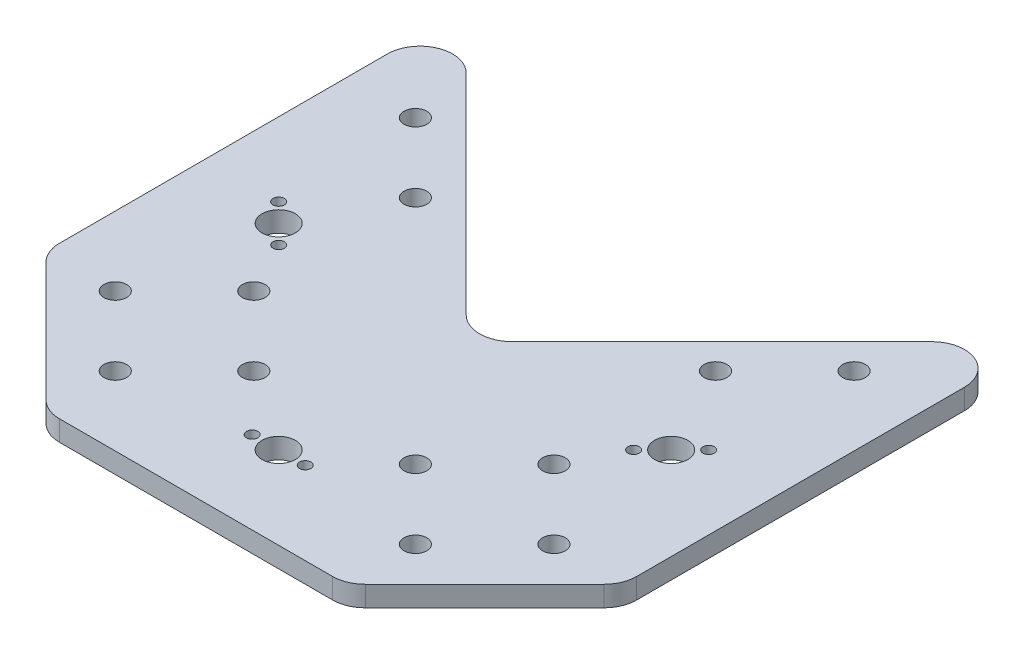
SolidWorks part; units mm, degrees
material "Acrylic (Medium-high impact)"
ref_plane "Front Plane" through (0, 0, 0) normal (0, 0, 1) x (1, 0, 0)
ref_plane "Top Plane" through (0, 0, 0) normal (0, 1, 0) x (1, 0, 0)
ref_plane "Right Plane" through (0, 0, 0) normal (1, 0, 0) x (0, 0, -1)
sketch "Sketch1" plane through (0, 0, 0) normal (0, 1, 0) x (1, 0, 0)
  line L0 (-112.2532, -112.2532) -> (-58.3717, -166.1347)
  line L1 (-112.2532, -112.2532) -> (-26.9408, -26.9408)
  line L2 (58.3717, -166.1347) -> (112.2532, -112.2532)
  line L3 (26.9408, -26.9408) -> (112.2532, -112.2532)
  line L4 (-112.2532, -112.2532) -> (-112.2532, 58.3717)
  line L5 (-112.2532, 58.3717) -> (0, -53.8815)
  line L6 (112.2532, -112.2532) -> (112.2532, 58.3717)
  line L7 (0, -53.8815) -> (112.2532, 58.3717)
  line L8 (-58.3717, -166.1347) -> (58.3717, -166.1347)
  line L9 (0, 0) -> (-53.8815, -53.8815) construction
  line L10 (0, 0) -> (53.8815, -53.8815) construction
  line L11 (-53.8815, -53.8815) -> (0, -107.7631) construction
  line L12 (53.8815, -53.8815) -> (0, -107.7631) construction
  line L13 (-58.3717, -139.194) -> (-85.3124, -112.2532) construction
  line L14 (-58.3717, -139.194) -> (-31.4309, -112.2532) construction
  line L15 (-85.3124, -112.2532) -> (-58.3717, -85.3124) construction
  line L16 (-31.4309, -112.2532) -> (-58.3717, -85.3124) construction
  line L17 (58.3717, -85.3124) -> (85.3124, -112.2532) construction
  line L18 (58.3717, -85.3124) -> (31.4309, -112.2532) construction
  line L19 (85.3124, -112.2532) -> (58.3717, -139.194) construction
  line L20 (31.4309, -112.2532) -> (58.3717, -139.194) construction
  line L21 (0, -53.8815) -> (0, 0) construction
  line L22 (-58.3717, -22.4506) -> (-85.3124, 4.4901) construction
  line L23 (58.3717, -22.4506) -> (85.3124, 4.4901) construction
  circle A0 centre (-85.3124, -112.2532) radius 4.4196
  circle A1 centre (-58.3717, -85.3124) radius 4.4196
  circle A2 centre (-31.4309, -112.2532) radius 4.4196
  circle A3 centre (-58.3717, -139.194) radius 4.4196
  circle A4 centre (31.4309, -112.2532) radius 4.4196
  circle A5 centre (58.3717, -85.3124) radius 4.4196
  circle A6 centre (85.3124, -112.2532) radius 4.4196
  circle A7 centre (58.3717, -139.194) radius 4.4196
  circle A8 centre (-85.3124, 4.4901) radius 4.4196
  circle A9 centre (-58.3717, -22.4506) radius 4.4196
  circle A10 centre (58.3717, -22.4506) radius 4.4196
  circle A11 centre (85.3124, 4.4901) radius 4.4196
  point P3 (0, -166.1347)
  dimension "D8" = 8.8392
  dimension "D1" = 82.55
  dimension "D2" = 76.2
  dimension "D3" = 38.1
  dimension "D4" = 76.2
  dimension "D5" = 38.1
  dimension "D6" = 25.4
  dimension "D7" = 19.05
  dimension "D9" = 38.1
  dimension "D10" = 19.05
extrude "Boss-Extrude1" add sketch "Sketch1" along normal blind 7.9375 contours L5 L4 L1 | L0 L8 L2 L3 L7 L5 L1 | L7 L3 L6
sketch "Sketch2" plane through (0, 7.9375, 0) normal (0, 1, 0) x (1, 0, 0)
  line L0 (-112.2532, 58.3717) -> (-112.2532, 51.1875)
  line L1 (-112.2532, -112.2532) -> (-112.2532, 58.3717) construction
  line L2 (-112.2532, 51.1875) -> (0, -61.0657)
  line L3 (0, -61.0657) -> (112.2532, 51.1875)
  line L4 (112.2532, -112.2532) -> (112.2532, 58.3717) construction
  line L5 (112.2532, 51.1875) -> (112.2532, 58.3717)
  line L6 (112.2532, 58.3717) -> (0, -53.8815)
  line L7 (0, -53.8815) -> (-112.2532, 58.3717)
  line L8 (-112.2532, 58.3717) -> (-112.0675, 58.9073)
  line M9 (0, -53.8815) -> (-112.2532, 58.3717)
  line M10 (-112.2532, 58.3717) -> (-112.2532, -112.2532)
  line M14 (112.2532, -112.2532) -> (112.2532, 58.3717)
  line M15 (112.2532, 58.3717) -> (0, -53.8815)
  dimension "D1" = 5.08
extrude "Cut-Extrude1" cut sketch "Sketch2" against normal through all contours L2 L3 M14 M15 M9 M10
fillet "Fillet1" radius 12.7 7 edges at (-112.2532, 3.9688, 112.2532) (-58.3717, 3.9688, 166.1347) (58.3717, 3.9688, 166.1347) (112.2532, 3.9688, 112.2532) (112.2532, 3.9688, -51.1875) (0, 3.9688, 61.0657) (-112.2532, 3.9688, -51.1875)
sketch "Sketch3" plane through (0, 7.9375, 0) normal (0, 1, 0) x (1, 0, 0)
  line L0 (-10.3187, -133.9973) -> (10.3187, -133.9973) construction
  line L1 (0, -7.1842) -> (-53.8815, -61.0657) construction
  line L2 (-69.0357, -64.9616) -> (-83.6286, -50.3686) construction
  line L3 (69.0357, -64.9616) -> (83.6286, -50.3686) construction
  line L4 (0, -133.9973) -> (-76.3322, -57.6651) construction
  line L5 (0, -7.1842) -> (53.8815, -61.0657) construction
  line L6 (-53.8815, -61.0657) -> (0, -114.9473) construction
  line L7 (53.8815, -61.0657) -> (0, -114.9473) construction
  line L8 (8.9803, -52.0855) -> (90.5729, 29.5072) construction
  line L9 (0, -133.9973) -> (76.3322, -57.6651) construction
  circle A0 centre (0, -133.9973) radius 6.477
  circle A1 centre (-10.3187, -133.9973) radius 2.2035
  circle A2 centre (10.3187, -133.9973) radius 2.2034
  circle A3 centre (-10.3187, -133.9973) radius 3.8418 construction
  circle A4 centre (10.3187, -133.9973) radius 3.8418 construction
  circle A5 centre (-76.3322, -57.6651) radius 6.477
  circle A6 centre (-69.0357, -64.9616) radius 2.2035
  circle A7 centre (-83.6286, -50.3686) radius 2.2034
  circle A8 centre (-69.0357, -64.9616) radius 3.8418 construction
  circle A9 centre (-83.6286, -50.3686) radius 3.8418 construction
  circle A10 centre (76.3322, -57.6651) radius 6.477
  circle A11 centre (69.0357, -64.9616) radius 2.2035
  circle A12 centre (83.6286, -50.3686) radius 2.2034
  circle A13 centre (69.0357, -64.9616) radius 3.8417 construction
  circle A14 centre (83.6286, -50.3686) radius 3.8417 construction
  point P6 (0, -133.9973)
  point P22 (-76.3322, -57.6651)
  point P31 (76.3322, -57.6651)
  point P34 (0, 0)
  dimension "D1" = 12.954
  dimension "D2" = 4.4069
  dimension "D3" = 10.3187
  dimension "D4" = 76.2
  dimension "D5" = 38.1
  dimension "D6" = 10.3187
  dimension "D7" = 10.3187
  dimension "D8" = 107.95
  dimension "D9" = 19.05
extrude "Cut-Extrude2" cut sketch "Sketch3" against normal through all
